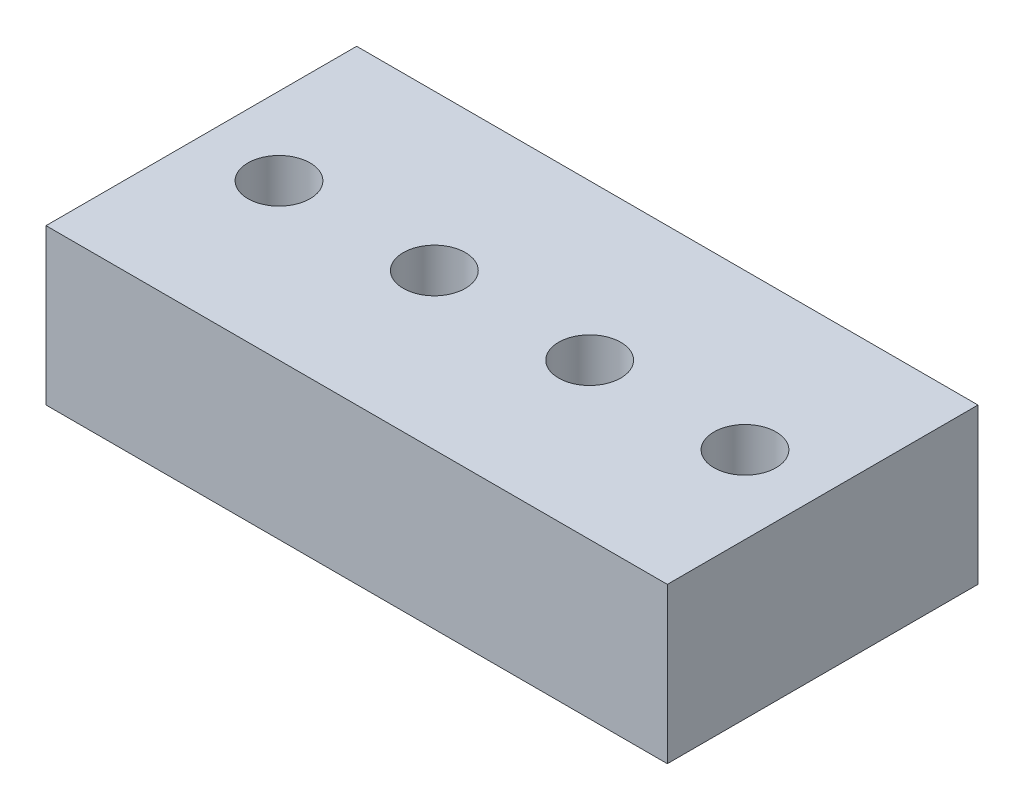
SolidWorks part; units mm, degrees
ref_plane "Front Plane" through (0, 0, 0) normal (0, 0, 1) x (1, 0, 0)
ref_plane "Top Plane" through (0, 0, 0) normal (0, 1, 0) x (1, 0, 0)
ref_plane "Right Plane" through (0, 0, 0) normal (1, 0, 0) x (0, 0, -1)
sketch "Sketch1" plane through (0, 0, 0) normal (0, 1, 0) x (1, 0, 0)
  line L0 (-40, -20) -> (40, -20)
  line L1 (40, -20) -> (40, 20)
  line L2 (40, 20) -> (-40, 20)
  line L3 (-40, 20) -> (-40, -20)
extrude "Boss-Extrude1" add sketch "Sketch1" along normal blind 20
sketch "Sketch2" plane through (0, 20, 0) normal (0, 1, 0) x (1, 0, 0)
  circle A0 centre (-30, 0) radius 4
extrude "Cut-Extrude1" cut sketch "Sketch2" against normal through all
pattern_linear "LPattern1" count 4 spacing 20 along (1, 0, 0) of "Cut-Extrude1"
